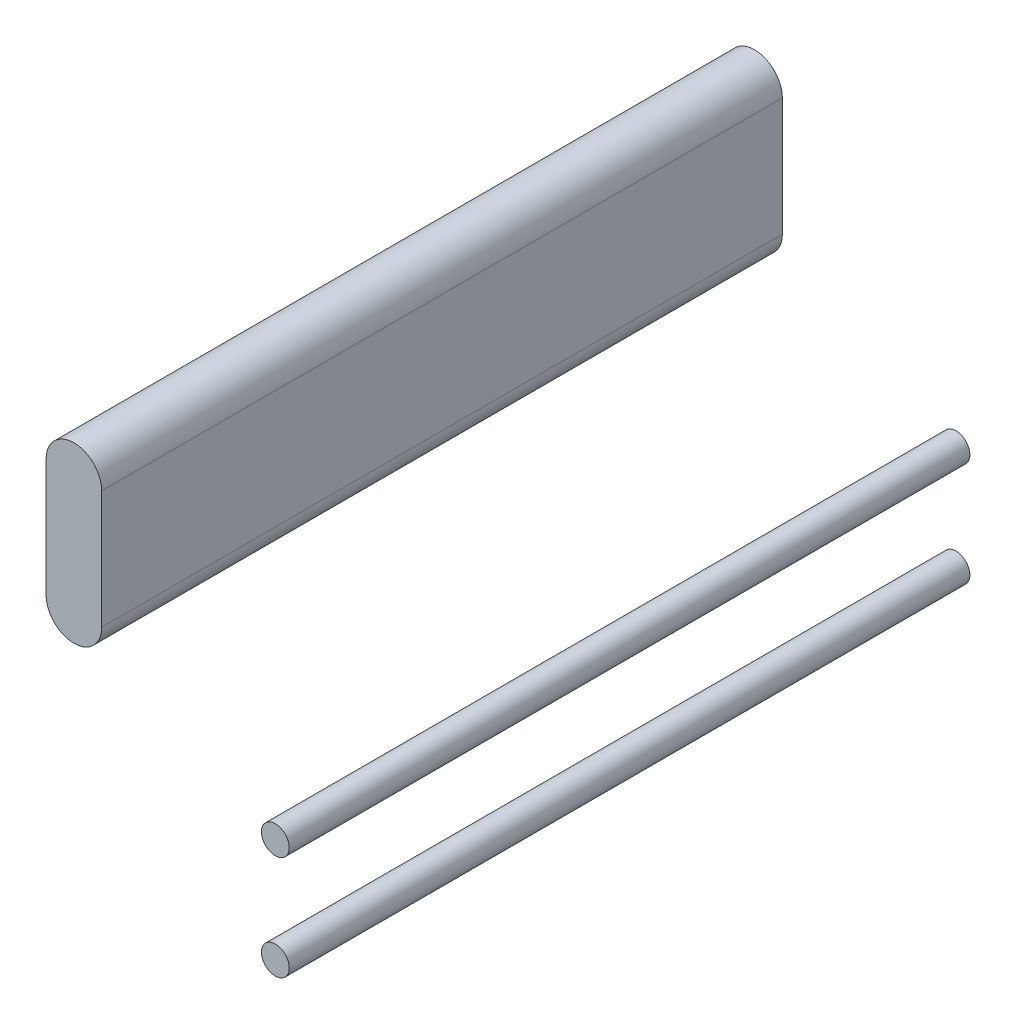
SolidWorks part; units mm, degrees
ref_plane "FP" through (0, 0, 0) normal (0, 0, 1) x (1, 0, 0)
ref_plane "TP" through (0, 0, 0) normal (0, 1, 0) x (1, 0, 0)
ref_plane "RP" through (0, 0, 0) normal (1, 0, 0) x (0, 0, -1)
sketch "Sketch2" plane through (0, 0, 0) normal (0, 0, 1) x (1, 0, 0)
  line L0 (4, 5) -> (4, 22) construction
  line L1 (-4, 22) -> (-4, 5) construction
  line L2 (4, 5) -> (4, 22)
  line L3 (-4, 22) -> (-4, 5)
  arc A0 (-4, 5) -> (4, 5) centre (0, 5) ccw construction
  arc A1 (4, 22) -> (-4, 22) centre (0, 22) ccw construction
  arc A2 (-4, 5) -> (4, 5) centre (0, 5) ccw
  arc A3 (4, 22) -> (-4, 22) centre (0, 22) ccw
  circle A4 centre (29, -9) radius 2 construction
  circle A5 centre (29, -9) radius 2
  circle A6 centre (29, -24) radius 2 construction
  circle A7 centre (29, -24) radius 2
extrude "Boss-Extrude1" add sketch "Sketch2" along normal blind 98
